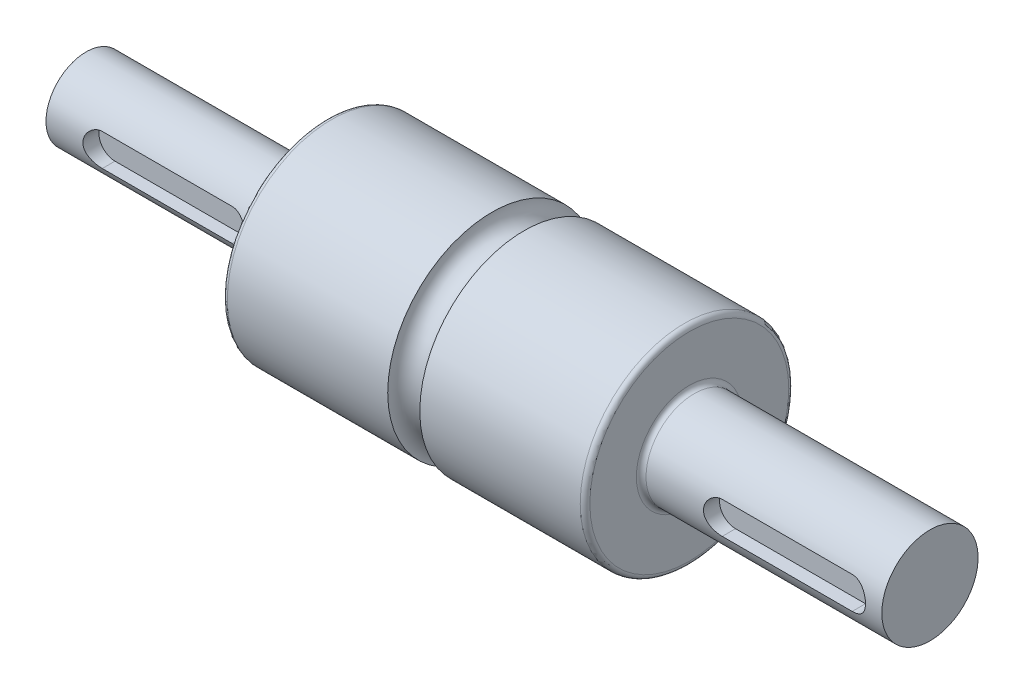
SolidWorks part; units mm, degrees
ref_plane "Alzado" through (0, 0, 0) normal (0, 0, 1) x (1, 0, 0)
ref_plane "Planta" through (0, 0, 0) normal (0, 1, 0) x (1, 0, 0)
ref_plane "Vista lateral" through (0, 0, 0) normal (1, 0, 0) x (0, 0, -1)
sketch "Croquis4" plane through (0, 0, 0) normal (0, 1, 0) x (1, 0, 0)
  line L0 (-131.5, 0) -> (131.5, 0) construction
  line L1 (-131.5, 0) -> (-131.5, 12.5)
  line L2 (-131.5, 12.5) -> (-58, 12.5)
  line L3 (-56.5, 14) -> (-56.5, 31)
  line L4 (-55, 32.5) -> (-5, 32.5)
  line L5 (56.5, 31) -> (56.5, 16.5)
  line L6 (58, 15) -> (131.5, 15)
  line L7 (131.5, 15) -> (131.5, 0)
  line L8 (0, 76.976) -> (0, 0) construction
  line L9 (5, 32.5) -> (55, 32.5)
  line L10 (-131.5, 0) -> (131.5, 0)
  arc A0 (-5, 32.5) -> (5, 32.5) centre (0, 32.5) ccw
  arc A1 (56.5, 16.5) -> (58, 15) centre (58, 16.5) ccw
  arc A2 (55, 32.5) -> (56.5, 31) centre (55, 31) cw
  arc A3 (-56.5, 31) -> (-55, 32.5) centre (-55, 31) cw
  arc A4 (-58, 12.5) -> (-56.5, 14) centre (-58, 14) ccw
  point P22 (-56.5, 12.5)
  dimension "D5" = 5
  dimension "D6" = 1.5
  dimension "D1" = 75
  dimension "D2" = 12.5
  dimension "D3" = 15
  dimension "D4" = 32.5
  dimension "D7" = 50
revolve "Revolución2" add sketch "Croquis4" angle 360 about L10
sketch "Croquis5" plane through (0, 0, 0) normal (0, 0, 1) x (1, 0, 0)
  line L0 (-94.75, 12.5) -> (-94.75, -12.5) construction
  line L1 (-131.5, 12.5) -> (-58, 12.5) construction
  line L2 (-131.5, 12.5) -> (-131.5, -12.5) construction
  line L3 (-131.5, -12.5) -> (-58, -12.5) construction
  line L4 (-58, 12.5) -> (-58, -12.5) construction
  line L5 (-131.5, 0) -> (-58, 0) construction
  line L6 (0, 75.8836) -> (0, -70.4308) construction
  line L7 (-115, -5) -> (-74.5, -5)
  line L8 (115, -5) -> (74.5, -5)
  line L9 (-115, 5) -> (-74.5, 5)
  line L10 (115, 5) -> (74.5, 5)
  line L11 (-115, -5) -> (-74.5, 5) construction
  line L12 (-115, 5) -> (-74.5, -5) construction
  arc A0 (-115, 5) -> (-115, -5) centre (-115, 0) ccw
  arc A1 (-74.5, 5) -> (-74.5, -5) centre (-74.5, 0) cw
  arc A2 (74.5, 5) -> (74.5, -5) centre (74.5, 0) ccw
  arc A3 (115, 5) -> (115, -5) centre (115, 0) cw
  point P10 (-94.75, 0)
  dimension "D1" = 40.5
  dimension "D2" = 10
extrude "Cortar-Extruir2" cut sketch "Croquis5" against normal blind 5 from offset 12.5 contours L7 A1 L9 A0
sketch "Croquis6" plane through (0, 0, 0) normal (0, 0, 1) x (1, 0, 0)
  line L0 (80.9034, 5) -> (121.4034, 5)
  line L1 (80.9034, -5) -> (121.4034, -5)
  line L2 (101.1534, 5) -> (101.1534, -5) construction
  arc A0 (80.9034, 5) -> (80.9034, -5) centre (80.9034, 0) ccw
  arc A1 (121.4034, 5) -> (121.4034, -5) centre (121.4034, 0) cw
extrude "Cortar-Extruir3" cut sketch "Croquis6" against normal blind 5 from offset 15
